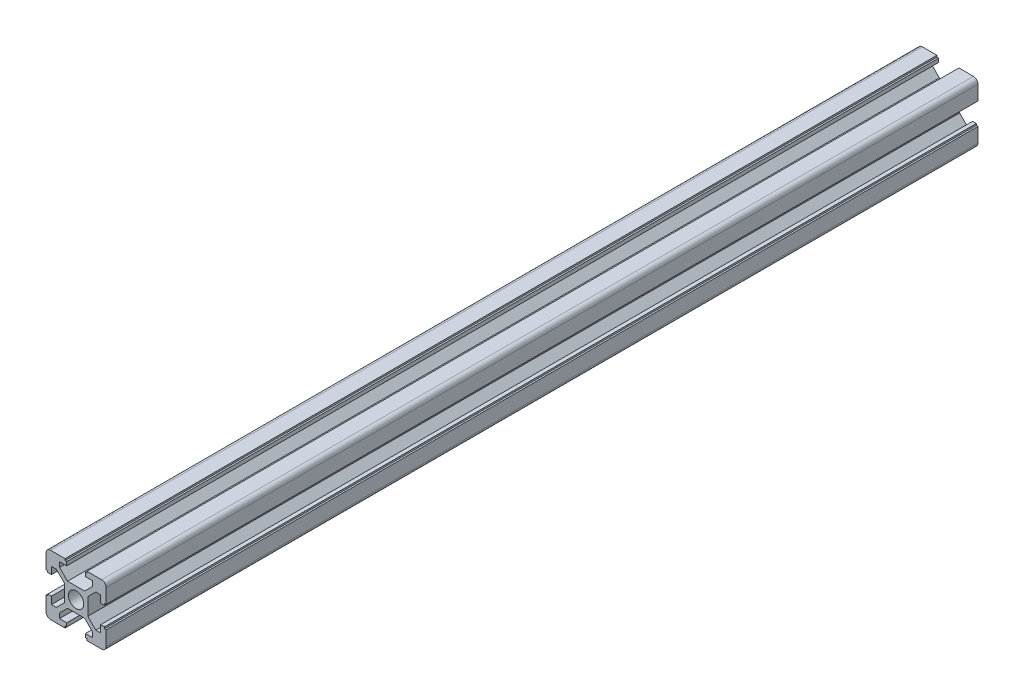
SolidWorks part; units mm, degrees
material "1060 Alloy"
ref_plane "Front Plane" through (0, 0, 0) normal (0, 0, 1) x (1, 0, 0)
ref_plane "Top Plane" through (0, 0, 0) normal (0, 1, 0) x (1, 0, 0)
ref_plane "Right Plane" through (0, 0, 0) normal (1, 0, 0) x (0, 0, -1)
sketch "Sketch2" plane through (0, 0, 0) normal (0, 0, 1) x (1, 0, 0)
  line L0 (-10, 10) -> (-3.65, 10)
  line L7 (-3.65, 10) -> (-3.65, 9.45)
  line L8 (-3.65, 9.45) -> (-3.1, 9.45)
  line L9 (-3.1, 9.45) -> (-3.1, 8.2)
  line L10 (-3.1, 8.2) -> (-5.5, 8.2)
  line L11 (-5.5, 8.2) -> (-5.5, 6.5607)
  line L18 (0, 0) -> (-10, 10) construction
  line L20 (-2.8393, 3.9) -> (-5.5, 6.5607)
  line L21 (-2.8393, 3.9) -> (0, 3.9)
  line L22 (-3.9, 2.8393) -> (-3.9, 0)
  line L23 (-3.9, 2.8393) -> (-6.5607, 5.5)
  line L24 (-8.2, 5.5) -> (-6.5607, 5.5)
  line L25 (-8.2, 3.1) -> (-8.2, 5.5)
  line L26 (-9.45, 3.1) -> (-8.2, 3.1)
  line L27 (-9.45, 3.65) -> (-9.45, 3.1)
  line L28 (-10, 3.65) -> (-9.45, 3.65)
  line L29 (-10, 10) -> (-10, 3.65)
  line L30 (2.8393, 3.9) -> (0, 3.9)
  line L31 (2.8393, 3.9) -> (5.5, 6.5607)
  line L32 (5.5, 8.2) -> (5.5, 6.5607)
  line L33 (3.1, 8.2) -> (5.5, 8.2)
  line L34 (3.1, 9.45) -> (3.1, 8.2)
  line L35 (3.65, 9.45) -> (3.1, 9.45)
  line L36 (10, 10) -> (3.65, 10)
  line L37 (10, 10) -> (10, 3.65)
  line L38 (10, 3.65) -> (9.45, 3.65)
  line L39 (9.45, 3.65) -> (9.45, 3.1)
  line L40 (9.45, 3.1) -> (8.2, 3.1)
  line L41 (8.2, 3.1) -> (8.2, 5.5)
  line L42 (8.2, 5.5) -> (6.5607, 5.5)
  line L43 (3.9, 2.8393) -> (6.5607, 5.5)
  line L44 (3.9, 2.8393) -> (3.9, 0)
  line L45 (3.65, 10) -> (3.65, 9.45)
  line L46 (3.9, -2.8393) -> (3.9, 0)
  line L47 (3.9, -2.8393) -> (6.5607, -5.5)
  line L48 (8.2, -5.5) -> (6.5607, -5.5)
  line L49 (8.2, -3.1) -> (8.2, -5.5)
  line L50 (9.45, -3.1) -> (8.2, -3.1)
  line L51 (9.45, -3.65) -> (9.45, -3.1)
  line L52 (10, -10) -> (10, -3.65)
  line L53 (10, -10) -> (3.65, -10)
  line L54 (3.65, -10) -> (3.65, -9.45)
  line L55 (3.65, -9.45) -> (3.1, -9.45)
  line L56 (3.1, -9.45) -> (3.1, -8.2)
  line L57 (3.1, -8.2) -> (5.5, -8.2)
  line L58 (5.5, -8.2) -> (5.5, -6.5607)
  line L59 (2.8393, -3.9) -> (5.5, -6.5607)
  line L60 (2.8393, -3.9) -> (0, -3.9)
  line L61 (10, -3.65) -> (9.45, -3.65)
  line L62 (-2.8393, -3.9) -> (0, -3.9)
  line L63 (-2.8393, -3.9) -> (-5.5, -6.5607)
  line L64 (-5.5, -8.2) -> (-5.5, -6.5607)
  line L65 (-3.1, -8.2) -> (-5.5, -8.2)
  line L66 (-3.1, -9.45) -> (-3.1, -8.2)
  line L67 (-3.65, -9.45) -> (-3.1, -9.45)
  line L68 (-10, -10) -> (-3.65, -10)
  line L69 (-10, -10) -> (-10, -3.65)
  line L70 (-10, -3.65) -> (-9.45, -3.65)
  line L71 (-9.45, -3.65) -> (-9.45, -3.1)
  line L72 (-9.45, -3.1) -> (-8.2, -3.1)
  line L73 (-8.2, -3.1) -> (-8.2, -5.5)
  line L74 (-8.2, -5.5) -> (-6.5607, -5.5)
  line L75 (-3.9, -2.8393) -> (-6.5607, -5.5)
  line L76 (-3.9, -2.8393) -> (-3.9, 0)
  line L77 (-3.65, -10) -> (-3.65, -9.45)
  dimension "D1" = 10
  dimension "D2" = 5.5
  dimension "D3" = 1.8
  dimension "D4" = 6.1
  dimension "D5" = 0.55
  dimension "D6" = 0.55
  dimension "D7" = 2.4
  dimension "D8" = 135
  dimension "D9" = 4
  dimension "D10" = 0.75
extrude "Boss-Extrude1" add sketch "Sketch2" against normal blind 290
sketch "Sketch3" plane through (0, 0, 0) normal (0, 0, 1) x (1, 0, 0)
  circle A0 centre (0, 0) radius 2.55
extrude "Cut-Extrude1" cut sketch "Sketch3" against normal through all contours A0
fillet "Fillet1" radius 1.5 4 edges at (-10, -10, -145) (10, -10, -145) (-10, 10, -145) (10, 10, -145)
